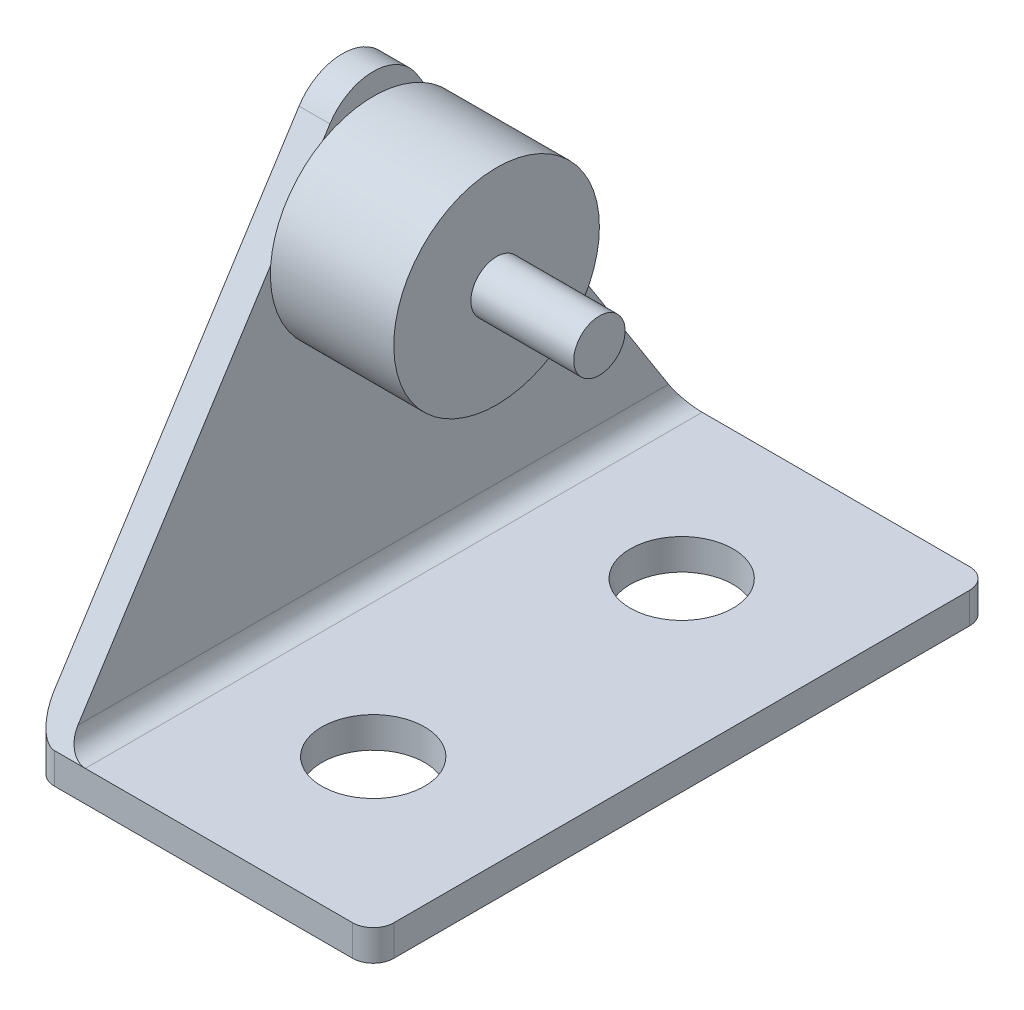
SolidWorks part; units mm, degrees
ref_plane "Front Plane" through (0, 0, 0) normal (0, 0, 1) x (1, 0, 0)
ref_plane "Top Plane" through (0, 0, 0) normal (0, 1, 0) x (1, 0, 0)
ref_plane "Right Plane" through (0, 0, 0) normal (1, 0, 0) x (0, 0, -1)
sketch "Sketch7" plane through (0, 0, 0) normal (0, 0, 1) x (1, 0, 0)
  line L0 (0, 0) -> (0, 63.5)
  line L1 (0, 0) -> (63.5, 0)
  line L3 (63.5, 3.81) -> (3.81, 3.81)
  line L4 (3.81, 3.81) -> (3.81, 63.5)
  line L5 (3.81, 63.5) -> (0, 63.5)
  line L6 (63.5, 3.81) -> (63.5, 0)
extrude "Boss-Extrude1" add sketch "Sketch7" along normal mid plane 76.2
sketch "Sketch8" plane through (3.81, 0, 0) normal (1, 0, 0) x (0, 0, -1)
  line L0 (-38.1, 3.81) -> (0, 63.5)
  line L1 (-38.1, 63.5) -> (38.1, 63.5) construction
  line L2 (0, 63.5) -> (38.1, 3.81)
  line L3 (0, 63.5) -> (38.1, 63.5)
  line L4 (38.1, 63.5) -> (38.1, 3.81)
  line L5 (0, 63.5) -> (-38.1, 63.5)
  line L6 (-38.1, 63.5) -> (-38.1, 3.81)
  line M1 (38.1, 3.81) -> (38.1, 63.5)
  line M2 (38.1, 63.5) -> (-38.1, 63.5)
  line M3 (-38.1, 63.5) -> (-38.1, 3.81)
extrude "Cut-Extrude2" cut sketch "Sketch8" against normal blind 76.2 contours L0 M3 M2 | L2 M2 M1
fillet "Fillet1" radius 6.35 1 edges at (1.905, 63.5, 0)
sketch "Sketch10" plane through (0, 3.81, 0) normal (0, 1, 0) x (1, 0, 0)
  line L0 (3.81, -38.1) -> (41.91, -38.1) construction
  line L1 (63.5, -38.1) -> (3.81, -38.1) construction
  line L2 (41.91, -38.1) -> (41.91, 38.1)
  line L3 (63.5, 38.1) -> (3.81, 38.1) construction
  line L4 (41.91, 38.1) -> (63.5, 38.1)
  line L5 (63.5, 38.1) -> (63.5, -38.1)
  line L6 (63.5, -38.1) -> (41.91, -38.1)
extrude "Cut-Extrude3" cut sketch "Sketch10" against normal blind 76.2
fillet "Fillet2" radius 2.54 4 edges at (0, 1.905, -38.1) (0, 1.905, 38.1) (41.91, 1.905, -38.1) (41.91, 1.905, 38.1)
fillet "Fillet3" radius 2.54 1 edges at (3.81, 3.81, 0)
sketch "Sketch11" plane through (3.81, 0, 0) normal (1, 0, 0) x (0, 0, -1)
  circle A0 centre (0, 42.692) radius 6.5024
extrude "Cut-Extrude4" cut sketch "Sketch11" against normal blind 76.2
sketch "Sketch12" plane through (0, 3.81, 0) normal (0, 1, 0) x (1, 0, 0)
  line L0 (3.81, 0) -> (22.86, 0)
  line L1 (3.81, -36.4787) -> (3.81, 36.4787) construction
  line L2 (22.86, 0) -> (22.86, 19.05)
  line L5 (22.86, 0) -> (22.86, -19.05)
  circle A0 centre (22.86, 19.05) radius 6.35
  circle A1 centre (22.86, -19.05) radius 6.35
extrude "Cut-Extrude5" cut sketch "Sketch12" against normal blind 76.2 contours A1 | A0
sketch "Sketch13" plane through (3.81, 0, 0) normal (1, 0, 0) x (0, 0, -1)
  circle A0 centre (0, 42.692) radius 12.7
extrude "Boss-Extrude2" add sketch "Sketch13" along normal blind 15.24
sketch "Sketch17" plane through (0, 0, 0) normal (-1, 0, 0) x (0, 0, 1)
  circle A0 centre (0, 42.692) radius 6.5024
extrude "Cut-Extrude6" cut sketch "Sketch17" against normal blind 6.604
sketch "Sketch18" plane through (19.05, 0, 0) normal (1, 0, 0) x (0, 0, -1)
  circle A0 centre (0, 42.692) radius 3.175
extrude "Boss-Extrude3" add sketch "Sketch18" along normal blind 12.7
